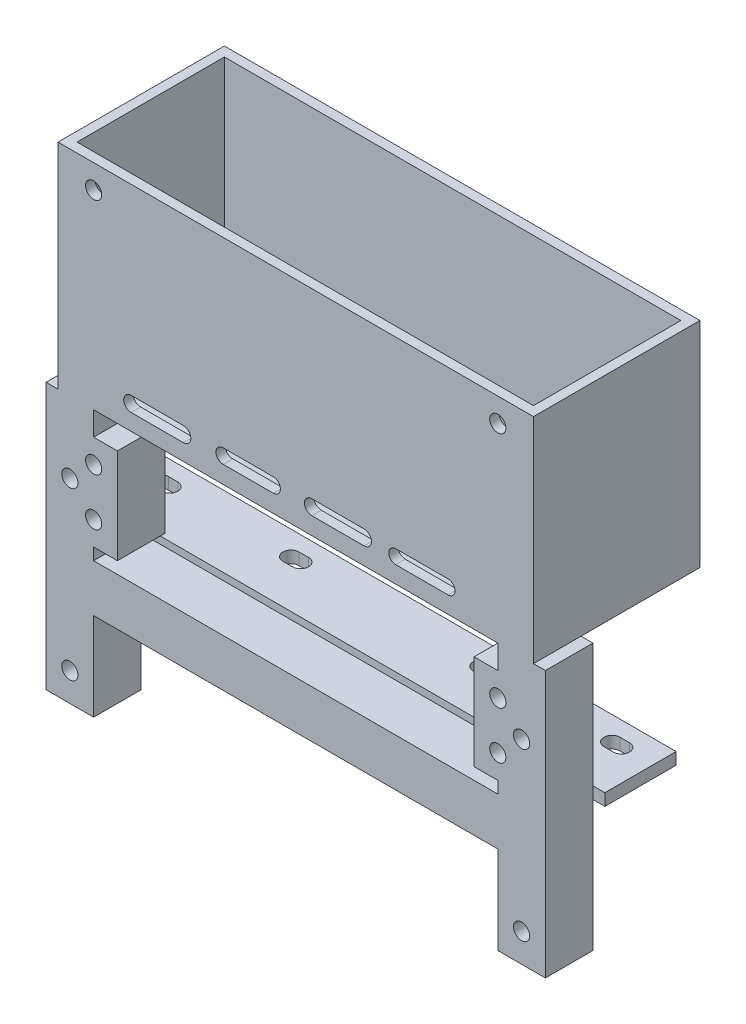
SolidWorks part; units mm, degrees
ref_plane "前视基准面" through (0, 0, 0) normal (0, 0, 1) x (1, 0, 0)
ref_plane "上视基准面" through (0, 0, 0) normal (0, 1, 0) x (1, 0, 0)
ref_plane "右视基准面" through (0, 0, 0) normal (1, 0, 0) x (0, 0, -1)
other "Configuration Table"
sketch "V3 box footprint 100 x 45 mm" plane through (0, 0, 0) normal (0, 0, 1) x (1, 0, 0)
  line L1 (-50, 0) -> (50, 0)
  line L2 (-50, 0) -> (-50, 45)
  line L3 (-50, 45) -> (50, 45)
  line L4 (50, 0) -> (50, 45)
extrude "V3 box height 35 mm" add sketch "V3 box footprint 100 x 45 mm" along normal blind 35
sketch "V3 rear opening 96 x 31 mm" plane through (0, 45, 0) normal (0, 1, 0) x (1, 0, 0)
  line L1 (-48, -2) -> (48, -2)
  line L2 (-48, -2) -> (-48, -33)
  line L3 (-48, -33) -> (48, -33)
  line L4 (48, -2) -> (48, -33)
extrude "V3 cavity all walls 2 mm" cut sketch "V3 rear opening 96 x 31 mm" against normal blind 43
sketch "V3 square beams 10 x 10 pitch 95 mm" plane through (0, 0, 0) normal (0, -1, 0) x (1, 0, 0)
  line L1 (-52.5, 25) -> (-42.5, 25)
  line L2 (-52.5, 25) -> (-52.5, 35)
  line L3 (-52.5, 35) -> (-42.5, 35)
  line L4 (-42.5, 25) -> (-42.5, 35)
  line L6 (42.5, 25) -> (52.5, 25)
  line L7 (42.5, 25) -> (42.5, 35)
  line L8 (42.5, 35) -> (52.5, 35)
  line L9 (52.5, 25) -> (52.5, 35)
extrude "V3 forward beam length 65 mm" add sketch "V3 square beams 10 x 10 pitch 95 mm" along normal blind 65
sketch "V3 left PCB ear profile" plane through (-42.5, 0, 0) normal (1, 0, 0) x (0, 0, -1)
  line L1 (-25, -25) -> (-35, -25)
  line L2 (-25, -25) -> (-25, -15)
  line L3 (-25, -15) -> (-35, -15)
  line L4 (-35, -25) -> (-35, -15)
extrude "V3 left inward ear 5 mm" add sketch "V3 left PCB ear profile" along normal blind 5
sketch "V3 right PCB ear profile" plane through (42.5, 0, 0) normal (-1, 0, 0) x (0, 0, 1)
  line L1 (25, -25) -> (35, -25)
  line L2 (25, -25) -> (25, -15)
  line L3 (25, -15) -> (35, -15)
  line L4 (35, -25) -> (35, -15)
extrude "V3 right inward ear 5 mm" add sketch "V3 right PCB ear profile" along normal blind 5
sketch "V3 PCB roof pair pitch 85 mm" plane through (0, 0, 35) normal (0, 0, 1) x (1, 0, 0)
  circle A0 centre (-42.5, 40) radius 1.7
  circle A1 centre (42.5, 40) radius 1.7
extrude "V3 M3 roof holes diameter 3.4 mm" cut sketch "V3 PCB roof pair pitch 85 mm" against normal blind 2
sketch "V3 PCB forward pair row spacing 60 mm" plane through (0, 0, 35) normal (0, 0, 1) x (1, 0, 0)
  circle A0 centre (-42.5, -20) radius 1.7
  circle A1 centre (42.5, -20) radius 1.7
extrude "V3 M3 PCB ear holes" cut sketch "V3 PCB forward pair row spacing 60 mm" against normal blind 10
sketch "V3 chassis top holes width 95 depth 40 mm" plane through (0, 0, 35) normal (0, 0, 1) x (1, 0, 0)
  circle A0 centre (-47.5, -55) radius 1.7
  circle A1 centre (-47.5, -15) radius 1.7
  circle A2 centre (47.5, -55) radius 1.7
  circle A3 centre (47.5, -15) radius 1.7
extrude "V3 M3 beam top bottom holes" cut sketch "V3 chassis top holes width 95 depth 40 mm" against normal blind 10
sketch "V3 hanging plate offset 26 thickness 2.5 mm" plane through (0, 0, 25) normal (0, 0, -1) x (-1, 0, 0)
  line L1 (55, -28.5) -> (-55, -28.5)
  line L2 (55, -28.5) -> (55, -26)
  line L3 (55, -26) -> (-55, -26)
  line L4 (-55, -28.5) -> (-55, -26)
extrude "V3 mounting plate downward 15 mm width 110" add sketch "V3 hanging plate offset 26 thickness 2.5 mm" along normal blind 15
sketch "V3 slots 6 mm below beam underside centers 20 and 47.5" plane through (0, -28.5, 0) normal (0, -1, 0) x (1, 0, 0)
  line L0 (-48.5, 19) -> (-46.5, 19) construction
  line L1 (-48.5, 20.7) -> (-46.5, 20.7)
  line L2 (-48.5, 17.3) -> (-46.5, 17.3)
  line L3 (-21, 19) -> (-19, 19) construction
  line L4 (-21, 20.7) -> (-19, 20.7)
  line L5 (-21, 17.3) -> (-19, 17.3)
  line L6 (19, 19) -> (21, 19) construction
  line L7 (19, 20.7) -> (21, 20.7)
  line L8 (19, 17.3) -> (21, 17.3)
  line L9 (46.5, 19) -> (48.5, 19) construction
  line L10 (46.5, 20.7) -> (48.5, 20.7)
  line L11 (46.5, 17.3) -> (48.5, 17.3)
  arc A0 (-48.5, 20.7) -> (-48.5, 17.3) centre (-48.5, 19) ccw
  arc A1 (-46.5, 17.3) -> (-46.5, 20.7) centre (-46.5, 19) ccw
  arc A2 (-21, 20.7) -> (-21, 17.3) centre (-21, 19) ccw
  arc A3 (-19, 17.3) -> (-19, 20.7) centre (-19, 19) ccw
  arc A4 (19, 20.7) -> (19, 17.3) centre (19, 19) ccw
  arc A5 (21, 17.3) -> (21, 20.7) centre (21, 19) ccw
  arc A6 (46.5, 20.7) -> (46.5, 17.3) centre (46.5, 19) ccw
  arc A7 (48.5, 17.3) -> (48.5, 20.7) centre (48.5, 19) ccw
  point P2 (-47.5, 19)
  point P7 (-20, 19)
  point P14 (20, 19)
  point P21 (47.5, 19)
  dimension "D1" = 3.4
  dimension "D2" = 2
  dimension "D3" = 3.4
  dimension "D4" = 2
  dimension "D5" = 3.4
  dimension "D6" = 2
  dimension "D7" = 3.4
  dimension "D8" = 2
extrude "Four horizontal slots 3.4 x 5.4 mm" cut sketch "V3 slots 6 mm below beam underside centers 20 and 47.5" against normal blind 2.5
sketch "草图1" plane through (0, 0, 35) normal (0, 0, 1) x (1, 0, 0)
  line L0 (-34.6201, 5) -> (-23.6201, 5) construction
  line L1 (-34.6201, 6.488) -> (-23.6201, 6.488)
  line L2 (-34.6201, 3.512) -> (-23.6201, 3.512)
  line L3 (21.03, 5) -> (32.03, 5) construction
  line L6 (21.03, 6.488) -> (32.03, 6.488)
  line L7 (21.03, 3.512) -> (32.03, 3.512)
  arc A0 (-34.6201, 6.488) -> (-34.6201, 3.512) centre (-34.6201, 5) ccw
  arc A1 (-23.6201, 3.512) -> (-23.6201, 6.488) centre (-23.6201, 5) ccw
  arc A4 (21.03, 6.488) -> (21.03, 3.512) centre (21.03, 5) ccw
  arc A5 (32.03, 3.512) -> (32.03, 6.488) centre (32.03, 5) ccw
  point P2 (-29.1201, 5)
  point P9 (26.53, 5)
sketch "草图2" plane through (0, 0, 0) normal (0, 0, -1) x (-1, 0, 0)
  line L0 (-32.03, 5) -> (-21.03, 5) construction
  line L1 (-32.03, 6.4595) -> (-21.03, 6.4595)
  line L2 (-32.03, 3.5405) -> (-21.03, 3.5405)
  line L3 (23.6201, 5) -> (34.6201, 5) construction
  line L4 (23.6201, 6.5587) -> (34.6201, 6.5587)
  line L5 (23.6201, 3.4413) -> (34.6201, 3.4413)
  arc A0 (-32.03, 6.4595) -> (-32.03, 3.5405) centre (-32.03, 5) ccw
  arc A1 (-21.03, 3.5405) -> (-21.03, 6.4595) centre (-21.03, 5) ccw
  arc A2 (23.6201, 6.5587) -> (23.6201, 3.4413) centre (23.6201, 5) ccw
  arc A3 (34.6201, 3.4413) -> (34.6201, 6.5587) centre (34.6201, 5) ccw
  point P4 (-26.53, 5)
  point P9 (29.1201, 5)
extrude "切除-拉伸1" cut sketch "草图2" against normal through all
sketch "H crossmember 10 x 10 mm at beam midpoint" plane through (-42.5, 0, 0) normal (1, 0, 0) x (0, 0, -1)
  line L1 (-25, -37.5) -> (-35, -37.5)
  line L2 (-25, -37.5) -> (-25, -27.5)
  line L3 (-25, -27.5) -> (-35, -27.5)
  line L4 (-35, -37.5) -> (-35, -27.5)
extrude "H crossmember 85 mm" add sketch "H crossmember 10 x 10 mm at beam midpoint" along normal blind 85
sketch "Beam cavities 6 mm wide preserving screw collars" plane through (0, 0, 35) normal (0, 0, 1) x (1, 0, 0)
  line L1 (-50.5, -65) -> (-44.5, -65)
  line L2 (-50.5, -65) -> (-50.5, -59)
  line L3 (-50.5, -59) -> (-44.5, -59)
  line L4 (-44.5, -65) -> (-44.5, -59)
  line L6 (-50.5, -51) -> (-44.5, -51)
  line L7 (-50.5, -51) -> (-50.5, -24)
  line L8 (-50.5, -24) -> (-44.5, -24)
  line L9 (-44.5, -51) -> (-44.5, -24)
  line L11 (-50.5, -11) -> (-44.5, -11)
  line L12 (-50.5, -11) -> (-50.5, -2)
  line L13 (-50.5, -2) -> (-44.5, -2)
  line L14 (-44.5, -11) -> (-44.5, -2)
  line L16 (44.5, -65) -> (50.5, -65)
  line L17 (44.5, -65) -> (44.5, -59)
  line L18 (44.5, -59) -> (50.5, -59)
  line L19 (50.5, -65) -> (50.5, -59)
  line L21 (44.5, -51) -> (50.5, -51)
  line L22 (44.5, -51) -> (44.5, -24)
  line L23 (44.5, -24) -> (50.5, -24)
  line L24 (50.5, -51) -> (50.5, -24)
  line L26 (44.5, -11) -> (50.5, -11)
  line L27 (44.5, -11) -> (44.5, -2)
  line L28 (44.5, -2) -> (50.5, -2)
  line L29 (50.5, -11) -> (50.5, -2)
extrude "Longitudinal beam walls 2 mm - inner height 6 mm" cut sketch "Beam cavities 6 mm wide preserving screw collars" against normal blind 6 from offset 2
sketch "H crossmember cavity connects both beam cavities" plane through (0, 0, 35) normal (0, 0, 1) x (1, 0, 0)
  line L1 (-44.5, -35.5) -> (44.5, -35.5)
  line L2 (-44.5, -35.5) -> (-44.5, -29.5)
  line L3 (-44.5, -29.5) -> (44.5, -29.5)
  line L4 (44.5, -35.5) -> (44.5, -29.5)
extrude "H crossmember walls 2 mm" cut sketch "H crossmember cavity connects both beam cavities" against normal blind 6 from offset 2
sketch "草图7" plane through (0, 0, 35) normal (0, 0, 1) x (1, 0, 0)
  line L0 (-15.2765, 5.1864) -> (-4.7235, 5.1864) construction
  line L1 (-15.2765, 6.6864) -> (-4.7235, 6.6864)
  line L2 (-15.2765, 3.6864) -> (-4.7235, 3.6864)
  line L3 (3.3727, 5.1864) -> (14.3727, 5.1864) construction
  line L4 (3.3727, 6.6864) -> (14.3727, 6.6864)
  line L5 (3.3727, 3.6864) -> (14.3727, 3.6864)
  arc A0 (-15.2765, 6.6864) -> (-15.2765, 3.6864) centre (-15.2765, 5.1864) ccw
  arc A1 (-4.7235, 3.6864) -> (-4.7235, 6.6864) centre (-4.7235, 5.1864) ccw
  arc A2 (3.3727, 6.6864) -> (3.3727, 3.6864) centre (3.3727, 5.1864) ccw
  arc A3 (14.3727, 3.6864) -> (14.3727, 6.6864) centre (14.3727, 5.1864) ccw
  point P2 (-10, 5.1864)
  point P7 (8.8727, 5.1864)
sketch "草图8" plane through (0, 0, 0) normal (0, 0, -1) x (-1, 0, 0)
  line L0 (-14.3727, 5.1864) -> (-3.3727, 5.1864) construction
  line L1 (-14.3727, 6.733) -> (-3.3727, 6.733)
  line L2 (-14.3727, 3.6397) -> (-3.3727, 3.6397)
  line L3 (4.7235, 5.1864) -> (15.2765, 5.1864) construction
  line L4 (4.7235, 6.6864) -> (15.2765, 6.6864)
  line L5 (4.7235, 3.6864) -> (15.2765, 3.6864)
  arc A0 (-14.3727, 6.733) -> (-14.3727, 3.6397) centre (-14.3727, 5.1864) ccw
  arc A1 (-3.3727, 3.6397) -> (-3.3727, 6.733) centre (-3.3727, 5.1864) ccw
  arc A2 (4.7235, 6.6864) -> (4.7235, 3.6864) centre (4.7235, 5.1864) ccw
  arc A3 (15.2765, 3.6864) -> (15.2765, 6.6864) centre (15.2765, 5.1864) ccw
  point P4 (-8.8727, 5.1864)
  point P9 (10, 5.1864)
extrude "切除-拉伸4" cut sketch "草图8" against normal through all
sketch "V6 extend 10 x 10 hollow beams with 2 mm walls" plane through (0, -65, 0) normal (0, -1, 0) x (1, 0, 0)
  line L1 (-52.5, 25) -> (-42.5, 25)
  line L2 (-52.5, 25) -> (-52.5, 35)
  line L3 (-52.5, 35) -> (-42.5, 35)
  line L4 (-42.5, 25) -> (-42.5, 35)
  line L6 (-50.5, 27) -> (-44.5, 27)
  line L7 (-50.5, 27) -> (-50.5, 33)
  line L8 (-50.5, 33) -> (-44.5, 33)
  line L9 (-44.5, 27) -> (-44.5, 33)
  line L11 (42.5, 25) -> (52.5, 25)
  line L12 (42.5, 25) -> (42.5, 35)
  line L13 (42.5, 35) -> (52.5, 35)
  line L14 (52.5, 25) -> (52.5, 35)
  line L16 (44.5, 27) -> (50.5, 27)
  line L17 (44.5, 27) -> (44.5, 33)
  line L18 (44.5, 33) -> (50.5, 33)
  line L19 (50.5, 27) -> (50.5, 33)
extrude "V6 hollow beam extensions 15 mm" add sketch "V6 extend 10 x 10 hollow beams with 2 mm walls" along normal blind 15
sketch "V6 four full-depth PCB pads centers x42.5 y-70 and -10" plane through (0, 0, 35) normal (0, 0, 1) x (1, 0, 0)
  line L1 (-52.5, -75) -> (-37.5, -75)
  line L2 (-52.5, -75) -> (-52.5, -65)
  line L3 (-52.5, -65) -> (-37.5, -65)
  line L4 (-37.5, -75) -> (-37.5, -65)
  line L6 (37.5, -75) -> (52.5, -75)
  line L7 (37.5, -75) -> (37.5, -65)
  line L8 (37.5, -65) -> (52.5, -65)
  line L9 (52.5, -75) -> (52.5, -65)
  line L11 (-52.5, -15) -> (-37.5, -15)
  line L12 (-52.5, -15) -> (-52.5, -5)
  line L13 (-52.5, -5) -> (-37.5, -5)
  line L14 (-37.5, -15) -> (-37.5, -5)
  line L16 (37.5, -15) -> (52.5, -15)
  line L17 (37.5, -15) -> (37.5, -5)
  line L18 (37.5, -5) -> (52.5, -5)
  line L19 (52.5, -15) -> (52.5, -5)
extrude "V6 solid screw pads with 5 mm inward ears" add sketch "V6 four full-depth PCB pads centers x42.5 y-70 and -10" against normal blind 10
sketch "V6 PCB holes 85 x 60 mm and retained chassis holes" plane through (0, 0, 35) normal (0, 0, 1) x (1, 0, 0)
  circle A0 centre (-42.5, -70) radius 1.7
  circle A1 centre (-42.5, -10) radius 1.7
  circle A2 centre (42.5, -70) radius 1.7
  circle A3 centre (42.5, -10) radius 1.7
  circle A4 centre (-47.5, -15) radius 1.7
  circle A5 centre (47.5, -15) radius 1.7
extrude "V6 four PCB M3 holes through reinforced beam pads" cut sketch "V6 PCB holes 85 x 60 mm and retained chassis holes" against normal blind 10
sketch "V7 retain rail envelopes 10 x 10 length 80 mm" plane through (0, 0, 35) normal (0, 0, 1) x (1, 0, 0)
  line L1 (-52.5, -80) -> (-42.5, -80)
  line L2 (-52.5, -80) -> (-52.5, 0)
  line L3 (-52.5, 0) -> (-42.5, 0)
  line L4 (-42.5, -80) -> (-42.5, 0)
  line L6 (42.5, -80) -> (52.5, -80)
  line L7 (42.5, -80) -> (42.5, 0)
  line L8 (42.5, 0) -> (52.5, 0)
  line L9 (52.5, -80) -> (52.5, 0)
extrude "V7 solid longitudinal beams" add sketch "V7 retain rail envelopes 10 x 10 length 80 mm" against normal blind 10
sketch "V7 retain H crossmember envelope" plane through (0, 0, 35) normal (0, 0, 1) x (1, 0, 0)
  line L1 (-42.5, -37.5) -> (42.5, -37.5)
  line L2 (-42.5, -37.5) -> (-42.5, -27.5)
  line L3 (-42.5, -27.5) -> (42.5, -27.5)
  line L4 (42.5, -37.5) -> (42.5, -27.5)
extrude "V7 solid H crossmember" add sketch "V7 retain H crossmember envelope" against normal blind 10
sketch "V7 preserve all ten existing beam M3 bores" plane through (0, 0, 35) normal (0, 0, 1) x (1, 0, 0)
  circle A0 centre (-47.5, -55) radius 1.7
  circle A1 centre (-47.5, -15) radius 1.7
  circle A2 centre (47.5, -55) radius 1.7
  circle A3 centre (47.5, -15) radius 1.7
  circle A4 centre (-42.5, -70) radius 1.7
  circle A5 centre (-42.5, -20) radius 1.7
  circle A6 centre (-42.5, -10) radius 1.7
  circle A7 centre (42.5, -70) radius 1.7
  circle A8 centre (42.5, -20) radius 1.7
  circle A9 centre (42.5, -10) radius 1.7
extrude "V7 restore chassis and PCB clearance bores" cut sketch "V7 preserve all ten existing beam M3 bores" against normal blind 10
sketch "V7 refill old mounting slots within unchanged plate" plane through (0, -28.5, 0) normal (0, -1, 0) x (1, 0, 0)
  line L1 (-55, 10) -> (55, 10)
  line L2 (-55, 10) -> (-55, 25)
  line L3 (-55, 25) -> (55, 25)
  line L4 (55, 10) -> (55, 25)
extrude "V7 close previous slot positions" add sketch "V7 refill old mounting slots within unchanged plate" against normal blind 2.5
sketch "V7 slot centers z15 - 10 mm below beam underside z25" plane through (0, -28.5, 0) normal (0, -1, 0) x (1, 0, 0)
  line L0 (-48.5, 15) -> (-46.5, 15) construction
  line L1 (-48.5, 16.7) -> (-46.5, 16.7)
  line L2 (-48.5, 13.3) -> (-46.5, 13.3)
  line L3 (-21, 15) -> (-19, 15) construction
  line L4 (-21, 16.7) -> (-19, 16.7)
  line L5 (-21, 13.3) -> (-19, 13.3)
  line L6 (19, 15) -> (21, 15) construction
  line L7 (19, 16.7) -> (21, 16.7)
  line L8 (19, 13.3) -> (21, 13.3)
  line L9 (46.5, 15) -> (48.5, 15) construction
  line L10 (46.5, 16.7) -> (48.5, 16.7)
  line L11 (46.5, 13.3) -> (48.5, 13.3)
  arc A0 (-48.5, 16.7) -> (-48.5, 13.3) centre (-48.5, 15) ccw
  arc A1 (-46.5, 13.3) -> (-46.5, 16.7) centre (-46.5, 15) ccw
  arc A2 (-21, 16.7) -> (-21, 13.3) centre (-21, 15) ccw
  arc A3 (-19, 13.3) -> (-19, 16.7) centre (-19, 15) ccw
  arc A4 (19, 16.7) -> (19, 13.3) centre (19, 15) ccw
  arc A5 (21, 13.3) -> (21, 16.7) centre (21, 15) ccw
  arc A6 (46.5, 16.7) -> (46.5, 13.3) centre (46.5, 15) ccw
  arc A7 (48.5, 13.3) -> (48.5, 16.7) centre (48.5, 15) ccw
  point P2 (-47.5, 15)
  point P7 (-20, 15)
  point P14 (20, 15)
  point P21 (47.5, 15)
  point P28 (0, 0)
  dimension "D1" = 3.4
  dimension "D2" = 2
  dimension "D3" = 3.4
  dimension "D4" = 2
  dimension "D5" = 3.4
  dimension "D6" = 2
  dimension "D7" = 3.4
  dimension "D8" = 2
extrude "V7 four horizontal slots 3.4 x 5.4 mm at 10 mm" cut sketch "V7 slot centers z15 - 10 mm below beam underside z25" against normal blind 2.5
sketch "V8 refill old chassis bore row y-55 before shortening" plane through (0, 0, 35) normal (0, 0, 1) x (1, 0, 0)
  line L1 (-49.5, -57) -> (-45.5, -57)
  line L2 (-49.5, -57) -> (-49.5, -53)
  line L3 (-49.5, -53) -> (-45.5, -53)
  line L4 (-45.5, -57) -> (-45.5, -53)
  line L6 (45.5, -57) -> (49.5, -57)
  line L7 (45.5, -57) -> (45.5, -53)
  line L8 (45.5, -53) -> (49.5, -53)
  line L9 (49.5, -57) -> (49.5, -53)
extrude "V8 close chassis holes that would break beam ends" add sketch "V8 refill old chassis bore row y-55 before shortening" against normal blind 10
sketch "V8 shorten both free ends by 24 mm" plane through (0, -80, 0) normal (0, -1, 0) x (1, 0, 0)
  line L1 (-55, 25) -> (55, 25)
  line L2 (-55, 25) -> (-55, 35)
  line L3 (-55, 35) -> (55, 35)
  line L4 (55, 25) -> (55, 35)
extrude "V8 solid beams length 56 mm preserve plate position" cut sketch "V8 shorten both free ends by 24 mm" against normal blind 24
sketch "V8 chassis pair y-50 with 6 mm end distance" plane through (0, 0, 35) normal (0, 0, 1) x (1, 0, 0)
  circle A0 centre (-47.5, -50) radius 1.7
  circle A1 centre (47.5, -50) radius 1.7
extrude "V8 chassis M3 holes moved 5 mm toward battery box" cut sketch "V8 chassis pair y-50 with 6 mm end distance" against normal blind 10
